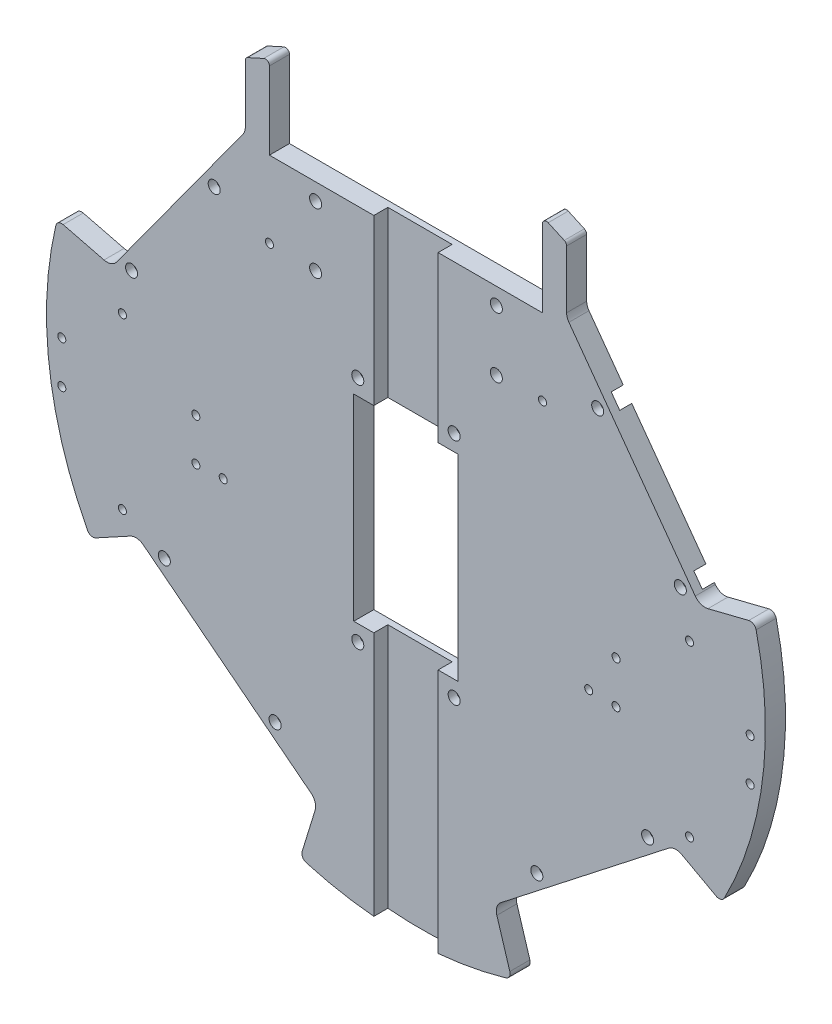
SolidWorks part; units mm, degrees
material "6061 合金"
ref_plane "前视基准面" through (0, 0, 0) normal (0, 0, 1) x (1, 0, 0)
ref_plane "上视基准面" through (0, 0, 0) normal (0, 1, 0) x (1, 0, 0)
ref_plane "右视基准面" through (0, 0, 0) normal (1, 0, 0) x (0, 0, -1)
other "Configuration Table"
sketch "草图1" plane through (0, 0, 0) normal (0, 0, 1) x (1, 0, 0)
  line L0 (0, 70) -> (0, -70) construction
  line L1 (-70, 0) -> (70, 0) construction
  line L2 (40.5729, 63.2472) -> (56.6312, 41.145)
  line L3 (56.6312, 41.145) -> (0, 0) construction
  line L4 (56.6312, 41.145) -> (72.029, 19.9517)
  line L6 (-34, 77) -> (34, 77)
  line L7 (22.5, 65) -> (-22.5, 65) construction
  line L8 (22.5, 65) -> (22.5, 50) construction
  line L9 (22.5, 50) -> (-22.5, 50) construction
  line L10 (-22.5, 65) -> (-22.5, 50) construction
  line L11 (0, 77) -> (0, 70) construction
  line L20 (0, 0) -> (43.0963, -55.1608) construction
  line L22 (43.0963, -55.1608) -> (23.6498, -70.354)
  line L23 (43.0963, -55.1608) -> (65.3853, -37.7466)
  line L24 (22.6293, -73.5997) -> (26.3029, -85.5477)
  line L25 (68.6695, -37.4773) -> (78.5614, -42.876)
  line L26 (40, 74) -> (40, 65.0106)
  line L27 (-68.6695, -37.4773) -> (-78.5614, -42.876)
  line L28 (-43.0963, -55.1608) -> (-65.3853, -37.7466)
  line L29 (-43.0963, -55.1608) -> (-23.6498, -70.354)
  line L30 (-22.6293, -73.5997) -> (-26.3029, -85.5477)
  line L31 (75.184, 18.8047) -> (86.8254, 21.7164)
  line L32 (-56.6312, 41.145) -> (-72.029, 19.9517)
  line L33 (-75.184, 18.8047) -> (-86.8254, 21.7164)
  line L34 (40, 74) -> (40, 80.064)
  line L35 (34, 77) -> (34, 82.7904)
  line L36 (40, 80.064) -> (34, 82.7904)
  line L37 (-40.5729, 63.2472) -> (-56.6312, 41.145)
  line L38 (-40, 74) -> (-40, 65.0106)
  line L39 (-40, 74) -> (-40, 80.064)
  line L40 (-40, 80.064) -> (-34, 82.7904)
  line L41 (-34, 77) -> (-34, 82.7904)
  arc A0 (-86.8254, 21.7164) -> (-78.5614, -42.876) centre (0, 0) ccw
  circle A1 centre (0, 0) radius 70 construction
  circle A5 centre (68.311, 19.9652) radius 1.5 construction
  circle A6 centre (47.7385, 48.2808) radius 1.5 construction
  circle A17 centre (-68.311, 19.9652) radius 1.5 construction
  arc A18 (40.5729, 63.2472) -> (40, 65.0106) centre (43, 65.0106) cw
  circle A19 centre (-47.7385, 48.2808) radius 1.5 construction
  circle A21 centre (32.5812, -59.569) radius 1.5 construction
  circle A22 centre (60.1616, -38.0208) radius 1.5 construction
  arc A23 (22.6293, -73.5997) -> (23.6498, -70.354) centre (25.4968, -72.718) cw
  arc A24 (68.6695, -37.4773) -> (65.3853, -37.7466) centre (67.2323, -40.1107) ccw
  arc A25 (78.5614, -42.876) -> (86.8254, 21.7164) centre (0, 0) ccw
  circle A26 centre (-32.5812, -59.569) radius 1.5 construction
  circle A27 centre (-60.1616, -38.0208) radius 1.5 construction
  arc A28 (-68.6695, -37.4773) -> (-65.3853, -37.7466) centre (-67.2323, -40.1107) cw
  arc A29 (-22.6293, -73.5997) -> (-23.6498, -70.354) centre (-25.4968, -72.718) ccw
  arc A30 (-26.3029, -85.5477) -> (26.3029, -85.5477) centre (0, 0) ccw
  arc A31 (75.184, 18.8047) -> (72.029, 19.9517) centre (74.4561, 21.715) cw
  arc A32 (-75.184, 18.8047) -> (-72.029, 19.9517) centre (-74.4561, 21.715) ccw
  circle A33 centre (0, 0) radius 89.5 construction
  arc A34 (-40.5729, 63.2472) -> (-40, 65.0106) centre (-43, 65.0106) ccw
  point P10 (56.6312, 41.145)
  point P16 (70.581, 24.7855)
  point P21 (0, 65)
  point P33 (40, 64.0358)
  point P38 (40, 77)
  point P43 (-40, 64.0358)
  point P55 (40, -64.0358)
  point P60 (22.0223, -71.6256)
  point P64 (66.9389, -36.5328)
  dimension "D1" = 179
  dimension "D2" = 140
  dimension "D7" = 3
  dimension "D14" = 24
  dimension "D3" = 40
  dimension "D4" = 3
  dimension "D15" = 3
  dimension "D17" = 3
  dimension "D21" = 11
  dimension "D5" = 6
  dimension "D23" = 3
  dimension "D26" = 3
  dimension "D29" = 3
  dimension "D30" = 3
  dimension "D31" = 179
  dimension "D32" = 77
  dimension "D6" = 3
  dimension "D8" = 54
  dimension "D9" = 45
  dimension "D10" = 15
  dimension "D11" = 22.5
  dimension "D12" = 12
  dimension "D13" = 12
  dimension "D16" = 3
  dimension "D18" = 90
  dimension "D19" = 11
  dimension "D20" = 38
  dimension "D22" = 3
  dimension "D24" = 3
  dimension "D25" = 24
  dimension "D27" = 57
  dimension "D28" = 12.5
  dimension "D33" = 6
extrude "整车底板外形拉伸" add sketch "草图1" along normal blind 5
fillet "圆角3" radius 1.5 1 edges at (78.5614, -42.876, 2.5)
fillet "圆角4" radius 1.5 1 edges at (26.3029, -85.5477, 2.5)
fillet "圆角5" radius 1.5 1 edges at (-26.3029, -85.5477, 2.5)
fillet "圆角6" radius 1.5 1 edges at (-78.5614, -42.876, 2.5)
fillet "圆角8" radius 1.5 1 edges at (86.8254, 21.7164, 2.5)
fillet "圆角9" radius 1.5 1 edges at (-86.8254, 21.7164, 2.5)
fillet "圆角10" radius 1 4 edges at (-40, 80.064, 2.5) (40, 80.064, 2.5) (-34, 82.7904, 2.5) (34, 82.7904, 2.5)
sketch "草图3" plane through (0, 0, 5) normal (0, 0, 1) x (1, 0, 0)
  line L0 (0, 77) -> (0, 27.068) construction
  line L1 (34, 77) -> (-34, 77) construction
  circle A0 centre (69, -8.5) radius 15.5
  circle A1 centre (-69, -8.5) radius 15.5
  dimension "D1" = 31
  dimension "D2" = 8.5
  dimension "D3" = 69
sketch "草图5" plane through (0, 0, 5) normal (0, 0, 1) x (1, 0, 0)
  line L0 (72.029, 19.9517) -> (40.5729, 63.2472) construction
  line L1 (0, 0) -> (56.6312, 41.145) construction
  line L2 (0, 77) -> (0, 0) construction
  line L3 (34, 77) -> (-34, 77) construction
  line L4 (0, 0) -> (43.0963, -55.1608) construction
  line L5 (23.6498, -70.354) -> (65.3853, -37.7466) construction
  circle A0 centre (47.7385, 48.2808) radius 1.5
  circle A1 centre (68.311, 19.9652) radius 1.5
  circle A2 centre (-68.311, 19.9652) radius 1.5
  circle A3 centre (-47.7385, 48.2808) radius 1.5
  circle A4 centre (60.1616, -38.0208) radius 1.5
  circle A5 centre (32.5812, -59.569) radius 1.5
  circle A6 centre (-60.1616, -38.0208) radius 1.5
  circle A7 centre (-32.5812, -59.569) radius 1.5
  dimension "D1" = 3
  dimension "D5" = 24
  dimension "D7" = 3
  dimension "D9" = 3
  dimension "D12" = 3
  dimension "D2" = 3
  dimension "D3" = 11
  dimension "D4" = 54
  dimension "D6" = 3
  dimension "D8" = 142
  dimension "D10" = 24
  dimension "D11" = 3
  dimension "D13" = 11
  dimension "D14" = 3
extrude "电机安装孔上部分" cut sketch "草图5" against normal blind 2
sketch "草图12" plane through (0, 0, 0) normal (0, 0, -1) x (-1, 0, 0)
  line L0 (0, 0) -> (56.6312, 41.145) construction
  line L1 (40.5729, 63.2472) -> (72.029, 19.9517) construction
  line L2 (0, 0) -> (0, 77) construction
  line L3 (-34, 77) -> (34, 77) construction
  line L4 (0, 0) -> (43.0963, -55.1608) construction
  line L5 (65.3853, -37.7466) -> (23.6498, -70.354) construction
  circle A0 centre (47.7385, 48.2808) radius 3.5
  circle A1 centre (68.311, 19.9652) radius 3.5
  circle A2 centre (-68.311, 19.9652) radius 3.5
  circle A3 centre (-47.7385, 48.2808) radius 3.5
  circle A4 centre (32.5812, -59.569) radius 3.5
  circle A5 centre (60.1616, -38.0208) radius 3.5
  circle A6 centre (13.527, -115.9287) radius 3.5
  circle A7 centre (-60.1616, -38.0208) radius 3.5
  circle A8 centre (-32.5812, -59.569) radius 3.5
  dimension "D1" = 7
  dimension "D5" = 7
  dimension "D11" = 7
  dimension "D12" = 7
  dimension "D2" = 11
  dimension "D3" = 3
  dimension "D4" = 24
  dimension "D6" = 3
  dimension "D7" = 11
  dimension "D8" = 24
  dimension "D9" = 3
  dimension "D10" = 3
extrude "电机安装孔下部分" cut sketch "草图12" against normal blind 3
sketch "草图7" plane through (0, 0, 5) normal (0, 0, 1) x (1, 0, 0)
  line L0 (-8, 77) -> (-8, -89.1417)
  line L1 (34, 77) -> (-34, 77) construction
  line L2 (-8, 77) -> (8, 77)
  line L4 (0, 0) -> (0, -22.89) construction
  line L5 (8, 77) -> (8, -89.1417)
  arc A1 (-24.8409, -85.9836) -> (24.8409, -85.9836) centre (0, 0) ccw construction
  arc A3 (-8, -89.1417) -> (8, -89.1417) centre (0, 0) ccw
  point P6 (0, -56)
  point P10 (0, 77)
  dimension "D1" = 16
extrude "挑球铲的槽" cut sketch "草图7" against normal blind 3.5
sketch "草图8" plane through (0, 0, 5) normal (0, 0, 1) x (1, 0, 0)
  line L0 (0, 77) -> (0, -5.3656) construction
  line L1 (8, 77) -> (-8, 77) construction
  line L2 (13, 21) -> (-13, 21)
  line L3 (-13, 21) -> (-13, -28)
  line L4 (-13, -28) -> (13, -28)
  line L5 (0, -5.3656) -> (0, -28) construction
  line L6 (-8, 77) -> (-34, 77) construction
  line L7 (13, 21) -> (13, -28)
  point P13 (0, 21)
  dimension "D1" = 49
  dimension "D2" = 13
  dimension "D3" = 56
extrude "安装电磁铁的槽" cut sketch "草图8" against normal blind 5
sketch "草图9" plane through (0, 0, 5) normal (0, 0, 1) x (1, 0, 0)
  line L0 (8, 21) -> (8, 77) construction
  line L1 (13, 21) -> (8, 21) construction
  line L2 (0, 0) -> (0, 32.0784) construction
  line L3 (-13, -3.5) -> (13, -3.5) construction
  line L4 (-13, 21) -> (-13, -28) construction
  line L5 (13, -28) -> (13, 21) construction
  circle A0 centre (12, 25) radius 1.5
  circle A1 centre (-12, 25) radius 1.5
  circle A2 centre (-12, -32) radius 1.5
  circle A3 centre (12, -32) radius 1.5
  dimension "D2" = 3
  dimension "D1" = 4
  dimension "D3" = 4
extrude "安装电磁铁的孔的上半部分" cut sketch "草图9" against normal blind 2
sketch "草图10" plane through (0, 0, 0) normal (0, 0, -1) x (-1, 0, 0)
  line L0 (8, 21) -> (8, 53.2712) construction
  line L1 (-13, 21) -> (13, 21) construction
  line L2 (0, 21) -> (0, 53.2712) construction
  line L3 (-13, -3.5) -> (13, -3.5) construction
  line L4 (-13, -28) -> (-13, 21) construction
  line L5 (13, 21) -> (13, -28) construction
  circle A0 centre (12, 25) radius 3.5
  circle A1 centre (-12, 25) radius 3.5
  circle A2 centre (12, -32) radius 3.5
  circle A3 centre (-12, -32) radius 3.5
  dimension "D4" = 7
  dimension "D1" = 8
  dimension "D2" = 4
  dimension "D3" = 4
extrude "安装电磁铁的孔下半部分" cut sketch "草图10" against normal blind 3
sketch "草图11" plane through (0, 0, 5) normal (0, 0, 1) x (1, 0, 0)
  line L0 (34, 77) -> (8, 77) construction
  line L1 (22.5, 57.8) -> (22.5, 42.8) construction
  line L2 (0, 77) -> (0, 50.9825) construction
  line L3 (8, 77) -> (-8, 77) construction
  circle A0 centre (22.5, 57.8) radius 1.5
  circle A1 centre (22.5, 42.8) radius 1.5
  circle A2 centre (-22.5, 42.8) radius 1.5
  circle A3 centre (-22.5, 57.8) radius 1.5
  dimension "D1" = 3
  dimension "D5" = 3
  dimension "D2" = 19.2
  dimension "D3" = 15
  dimension "D4" = 45
extrude "嘴部安装孔上部分" cut sketch "草图11" against normal blind 5
sketch "草图14" plane through (0, 0, 0) normal (0, 0, -1) x (-1, 0, 0)
  line L0 (34, 77) -> (34, 73)
  line L1 (-34, 77) -> (-34, 73)
  line L2 (-34, 73) -> (34, 73)
  line L3 (-34, 77) -> (34, 77)
extrude "绘画时嘴部过远，切削以作补偿" cut sketch "草图14" against normal blind 10
sketch "草图15" plane through (0, 0, 5) normal (0, 0, 1) x (1, 0, 0)
  line L0 (0, 73) -> (0, 23.218) construction
  line L1 (-8, 73) -> (8, 73) construction
  line L2 (-34, 73) -> (-8, 73) construction
  circle A2 centre (-45.5, -13.5) radius 1
  circle A3 centre (-34, 43) radius 1
  circle A4 centre (34, 43) radius 1
  circle A5 centre (45.5, -13.5) radius 1
  dimension "D1" = 2
  dimension "D2" = 68
  dimension "D3" = 30
  dimension "D5" = 2
  dimension "D4" = 56.5
  dimension "D6" = 91
extrude "电池盒安装孔" cut sketch "草图15" against normal blind 4
cosmetic thread "装饰螺纹线9" parameters "D2"=3
cosmetic thread "装饰螺纹线10" parameters "D2"=3
cosmetic thread "装饰螺纹线11" parameters "D2"=3
cosmetic thread "装饰螺纹线12" parameters "D2"=3
sketch "草图16" plane through (0, 0, 5) normal (0, 0, 1) x (1, 0, 0)
  line L13 (-70.6, 9.5) -> (70.6, 9.5) construction
  line L14 (-70.6, 9.5) -> (-70.6, -32.7) construction
  line L15 (-70.6, -32.7) -> (70.6, -32.7) construction
  line L16 (70.6, 9.5) -> (70.6, -32.7) construction
  line L17 (-8, 73) -> (8, 73) construction
  circle A0 centre (-70.6, -32.7) radius 1
  circle A1 centre (-70.6, 9.5) radius 1
  circle A2 centre (70.6, 9.5) radius 1
  circle A3 centre (70.6, -32.7) radius 1
  point P1 (0, 0)
  dimension "D6" = 2
  dimension "D1" = 141.2
  dimension "D2" = 42.2
  dimension "D3" = 63.5
  dimension "D4" = 70.6
extrude "电路板安装孔" cut sketch "草图16" against normal blind 4
cosmetic thread "装饰螺纹线1" parameters "D2"=3
cosmetic thread "装饰螺纹线2" parameters "D2"=3
cosmetic thread "装饰螺纹线3" parameters "D2"=3
cosmetic thread "装饰螺纹线4" parameters "D2"=3
sketch "草图17" plane through (0, 0, 5) normal (0, 0, 1) x (1, 0, 0)
  line L0 (0, 35) -> (0, -10.081) construction
  line L1 (52.31, -13.7624) -> (85.69, -13.7624) construction
  line L2 (52.31, -13.7624) -> (52.31, -3.2376) construction
  line L3 (52.31, -3.2376) -> (85.69, -3.2376) construction
  line L4 (85.69, -13.7624) -> (85.69, -3.2376) construction
  line L5 (52.31, -13.7624) -> (85.69, -3.2376) construction
  line L6 (52.31, -3.2376) -> (85.69, -13.7624) construction
  circle A1 centre (85.69, -3.2376) radius 1
  circle A2 centre (85.69, -13.7624) radius 1
  circle A3 centre (52.31, -13.7624) radius 1
  circle A4 centre (52.31, -3.2376) radius 1
  circle A5 centre (-52.31, -13.7624) radius 1
  circle A7 centre (-85.69, -3.2376) radius 1
  circle A8 centre (-52.31, -3.2376) radius 1
  circle A9 centre (-85.69, -13.7624) radius 1
  point P0 (69, -8.5)
  dimension "D2" = 2
  dimension "D1" = 35
  dimension "D3" = 35
extrude "电容座" cut sketch "草图17" against normal blind 4
cosmetic thread "装饰螺纹线13" parameters "D2"=3
cosmetic thread "装饰螺纹线14" parameters "D2"=3
cosmetic thread "装饰螺纹线15" parameters "D2"=3
cosmetic thread "装饰螺纹线17" parameters "D2"=3
cosmetic thread "装饰螺纹线18" parameters "D2"=3
cosmetic thread "装饰螺纹线19" parameters "D2"=3
cosmetic thread "装饰螺纹线20" parameters "D2"=3
cosmetic thread "装饰螺纹线21" parameters "D2"=3
sketch "草图18" plane through (0, 0, 0) normal (0, 0, -1) x (-1, 0, 0)
  circle A0 centre (-22.5, 57.8) radius 3.5
  circle A1 centre (-22.5, 42.8) radius 3.5
  circle A2 centre (22.5, 42.8) radius 3.5
  circle A3 centre (22.5, 57.8) radius 3.5
  dimension "D1" = 7
extrude "嘴部安装孔下部分" cut sketch "草图18" against normal blind 2
extrude "凸台-拉伸1" [suppressed] add sketch "草图3" along normal blind 45
sketch "草图19" plane through (0, 0, 5) normal (0, 0, 1) x (1, 0, 0)
  line L3 (-34, 73) -> (34, 73)
  line L4 (34, 73) -> (34, 62)
  line L5 (34, 62) -> (-34, 62)
  line L6 (-34, 62) -> (-34, 73)
  dimension "D1" = 11
extrude "切除-拉伸3" cut sketch "草图19" against normal mid plane 10
